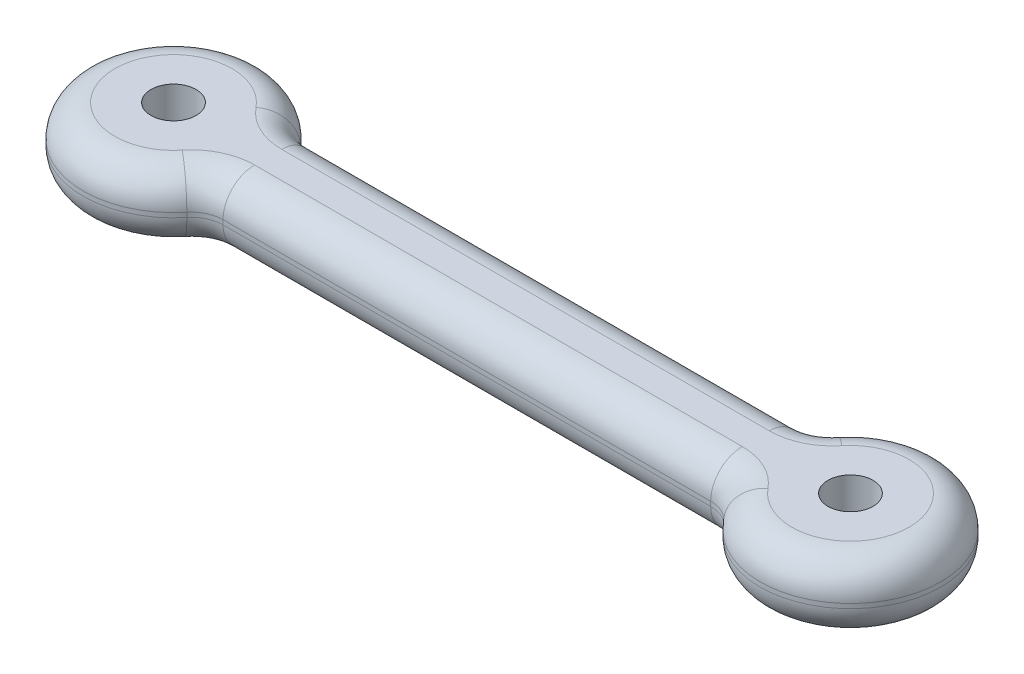
SolidWorks part; units mm, degrees
material "Oak"
ref_plane "Front" through (0, 0, 0) normal (0, 0, 1) x (1, 0, 0)
ref_plane "Top" through (0, 0, 0) normal (0, 1, 0) x (1, 0, 0)
ref_plane "Right" through (0, 0, 0) normal (1, 0, 0) x (0, 0, -1)
sketch "Sketch1" plane through (0, 0, 0) normal (0, 1, 0) x (1, 0, 0)
  line L0 (-144.2363, 0) -> (137.1621, 0) construction
  line L1 (0, 85.0876) -> (0, -80.7645) construction
  line L2 (57.6795, 10) -> (-57.6795, 10)
  line L3 (57.6795, -10) -> (-57.6795, -10)
  arc A0 (-57.6795, 10) -> (-57.6795, -10) centre (-75, 0) ccw
  arc A1 (57.6795, 10) -> (57.6795, -10) centre (75, 0) cw
  point P11 (0, -10)
  point P12 (0, 10)
  dimension "D2" = 40
  dimension "D1" = 10
  dimension "D3" = 75
extrude "Boss-Extrude1" add sketch "Sketch1" along normal blind 15
hole_wizard "Ø1.0mm Dowel Hole1" positions "Sketch3" profile "Sketch2" hole size "Ø1.0" standard "ANSI Metric" end condition through all
sketch "Sketch3" plane through (0, 15, 0) normal (0, 1, 0) x (1, 0, 0)
  arc A0 (-57.6795, 10) -> (-57.6795, -10) centre (-75, 0) ccw construction
  arc A1 (57.6795, -10) -> (57.6795, 10) centre (75, 0) ccw construction
  point P0 (-75, 0)
  point P2 (75, 0)
  dimension "D1" = 0
  dimension "D2" = 0
sketch "Sketch2" plane through (-75, 15, 0) normal (1, 0, 0) x (0, 0, 1)
  line L0 (0, 0) -> (0, 15)
  line L1 (0, 15) -> (5, 15)
  line L2 (5, 15) -> (5, 0)
  line L5 (5, 0) -> (0, 0)
  line L11 (0, -6.35) -> (0, 107.95) construction
  dimension "Thru Hole Dia." = 10
  dimension "Thru Hole Depth" = 15
fillet "Fillet1" radius 7 12 edges at (95, 15, 0) (95, 0, 0) (57.6795, 7.5, -10) (0, 15, -10) (0, 0, -10) (0, 15, 10) (57.6795, 7.5, 10) (0, 0, 10) (-57.6795, 7.5, -10) (-95, 15, 0) (-57.6795, 7.5, 10) (-95, 0, 0)
scale "Escala1" scale about centroid uniform scaling yes scale factor 0.2
